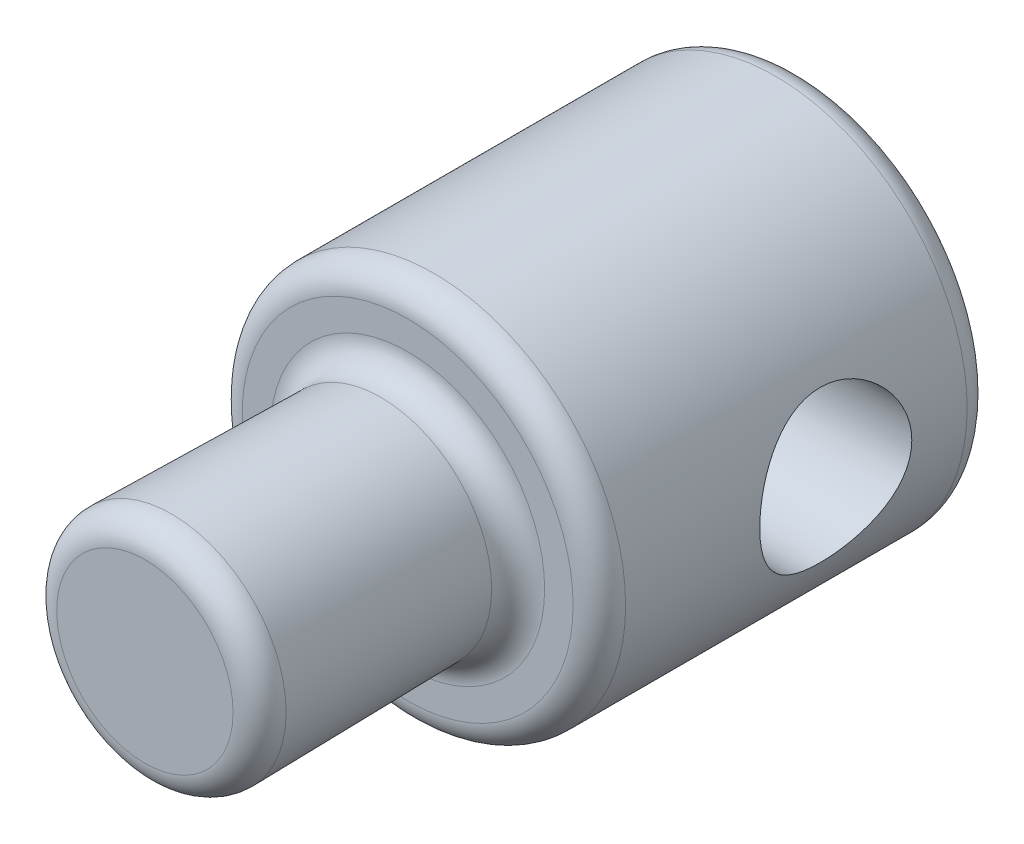
SolidWorks part; units mm, degrees
ref_plane "Plan de face" through (0, 0, 0) normal (0, 0, 1) x (1, 0, 0)
ref_plane "Plan de dessus" through (0, 0, 0) normal (0, 1, 0) x (1, 0, 0)
ref_plane "Plan de droite" through (0, 0, 0) normal (1, 0, 0) x (0, 0, -1)
sketch "Esquisse1" plane through (0, 0, 0) normal (0, 0, 1) x (1, 0, 0)
  circle A0 centre (0, 0) radius 3.65
  dimension "D1" = 7.3
extrude "Boss.-Extru.1" add sketch "Esquisse1" along normal blind 7.5
ref_plane "Plan1" through (4, 0, 0) normal (1, 0, 0) x (0, 0, -1)
sketch "Esquisse2" plane through (4, 0, 0) normal (1, 0, 0) x (0, 0, -1)
  circle A0 centre (-3, 0) radius 1.45
  dimension "D1" = 2.9
  dimension "D2" = 3
extrude "Enlèv. mat.-Extru.1" cut sketch "Esquisse2" against normal blind 7.2 draft 0.5
sketch "Esquisse3" plane through (0, 0, 7.5) normal (0, 0, 1) x (1, 0, 0)
  circle A0 centre (0, 0) radius 2.1
  dimension "D1" = 4.2
extrude "Boss.-Extru.2" add sketch "Esquisse3" along normal blind 5 draft 1 draft outward yes
fillet "Congé2" radius 0.5 4 edges at (2.1, 0, 7.5) (2.1873, 0, 12.5) (3.65, 0, 7.5) (3.65, 0, 0)
